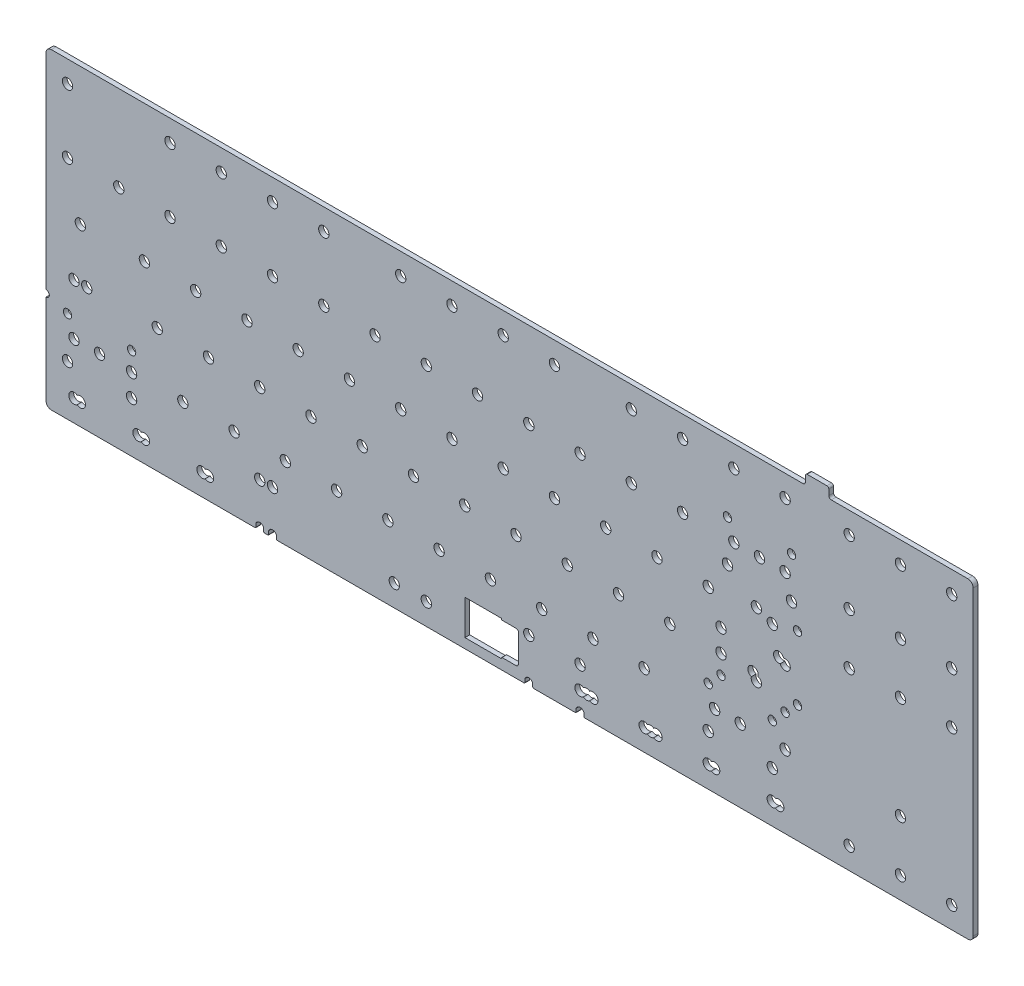
SolidWorks part; units mm, degrees
ref_plane "Front Plane" through (0, 0, 0) normal (0, 0, 1) x (1, 0, 0)
ref_plane "Top Plane" through (0, 0, 0) normal (0, 1, 0) x (1, 0, 0)
ref_plane "Right Plane" through (0, 0, 0) normal (1, 0, 0) x (0, 0, -1)
sketch "Model" plane through (0, 0, 0) normal (0, 0, 1) x (1, 0, 0)
  line L0 (147.7, -67.6) -> (161.2775, -67.6)
  line L1 (161.3, -67.8) -> (161.3, -67.9)
  line L2 (161.5, -68.1) -> (166.7, -68.1)
  line L3 (167.6, -69) -> (167.6, -79.2)
  line L4 (166.7, -80.1) -> (161.5, -80.1)
  line L5 (161.3, -80.3) -> (161.3, -80.4)
  line L6 (161.2775, -80.6) -> (147.7, -80.6)
  line L7 (147.7, -80.6) -> (147.7, -67.6)
  line L12 (273.3562, 31.8125) -> (-6, 31.8125)
  line L13 (-8, 29.8125) -> (-8, -46.4)
  line L14 (-7.998, -48.85) -> (-8, -48.85)
  line L15 (-8, -48.85) -> (-8, -82.2)
  line L16 (-6, -84.2) -> (69.7, -84.2)
  line L17 (70, -83.9) -> (70, -82.6265)
  line L18 (74.75, -82.6523) -> (74.75, -83.9)
  line L19 (74.45, -84.2) -> (73.2, -84.2)
  line L20 (72.9, -83.9) -> (72.9, -82.6795)
  line L21 (170, -82.6523) -> (170, -83.9)
  line L22 (169.7, -84.2) -> (77.95, -84.2)
  line L23 (77.65, -83.9) -> (77.65, -82.6523)
  line L24 (189.05, -82.6523) -> (189.05, -83.9)
  line L25 (188.75, -84.2) -> (173.2, -84.2)
  line L26 (172.9, -83.9) -> (172.9, -82.6523)
  line L27 (283.8562, 31.8125) -> (334.6125, 31.8125)
  line L28 (336.6125, 29.8125) -> (336.6125, -82.2)
  line L29 (334.6125, -84.2) -> (192.25, -84.2)
  line L30 (191.95, -83.9) -> (191.95, -82.6523)
  line L31 (282.9563, 32.7125) -> (282.9563, 34.85)
  line L32 (282.2563, 35.55) -> (274.9563, 35.55)
  line L33 (274.2563, 34.85) -> (274.2563, 32.7125)
  circle A0 centre (223.8375, -38.1) radius 1.925
  circle A1 centre (176.2125, -57.15) radius 1.925
  circle A2 centre (209.55, 0) radius 1.925
  circle A3 centre (195.2625, -57.15) radius 1.925
  circle A4 centre (214.3125, -57.15) radius 1.925
  circle A5 centre (190.5, 0) radius 1.925
  circle A6 centre (19.05, 0) radius 1.925
  circle A7 centre (38.1, 0) radius 1.925
  circle A8 centre (57.15, 0) radius 1.925
  circle A9 centre (76.2, 0) radius 1.925
  circle A10 centre (95.25, 0) radius 1.925
  circle A11 centre (114.3, 0) radius 1.925
  circle A12 centre (133.35, 0) radius 1.925
  circle A13 centre (152.4, 0) radius 1.925
  circle A14 centre (171.45, 0) radius 1.925
  circle A15 centre (204.7875, -38.1) radius 1.925
  circle A16 centre (228.6, 0) radius 1.925
  circle A17 centre (33.3375, -38.1) radius 1.925
  circle A18 centre (119.0625, -57.15) radius 1.925
  circle A19 centre (266.7, 0) radius 1.925
  circle A20 centre (80.9625, -57.15) radius 1.925
  circle A21 centre (2.3813, -38.1) radius 1.925
  circle A22 centre (7.1438, -38.1) radius 1.925
  circle A23 centre (71.4375, -38.1) radius 1.925
  circle A24 centre (290.5125, -19.05) radius 1.925
  circle A25 centre (309.5625, -76.2) radius 1.925
  circle A26 centre (66.675, -19.05) radius 1.925
  circle A27 centre (309.5625, -19.05) radius 1.925
  arc A28 (256.6362, -38.658) -> (254.1764, -39.9233) centre (254.7938, -38.1) ccw
  circle A29 centre (0, 23.8125) radius 1.925
  circle A30 centre (90.4875, -38.1) radius 1.925
  circle A31 centre (38.1, 23.8125) radius 1.925
  circle A32 centre (57.15, 23.8125) radius 1.925
  circle A33 centre (76.2, 23.8125) radius 1.925
  circle A34 centre (95.25, 23.8125) radius 1.925
  circle A35 centre (123.825, 23.8125) radius 1.925
  circle A36 centre (142.875, 23.8125) radius 1.925
  circle A37 centre (161.925, 23.8125) radius 1.925
  circle A38 centre (180.975, 23.8125) radius 1.925
  circle A39 centre (209.55, 23.8125) radius 1.925
  circle A40 centre (228.6, 23.8125) radius 1.925
  circle A41 centre (247.65, 23.8125) radius 1.925
  circle A42 centre (266.7, 23.8125) radius 1.925
  circle A43 centre (266.7, -57.15) radius 1.925
  circle A44 centre (109.5375, -38.1) radius 1.925
  circle A45 centre (128.5875, -38.1) radius 1.925
  circle A46 centre (309.5625, 0) radius 1.925
  circle A47 centre (161.925, -19.05) radius 1.925
  circle A48 centre (290.5125, 0) radius 1.925
  circle A49 centre (23.8125, -57.15) radius 1.925
  circle A50 centre (147.6375, -38.1) radius 1.925
  circle A51 centre (166.6875, -38.1) radius 1.925
  circle A52 centre (185.7375, -38.1) radius 1.925
  arc A53 (51.1969, -74.6874) -> (51.1969, -77.7126) centre (50.0063, -76.2) ccw
  arc A54 (51.1969, -77.7126) -> (51.1969, -74.6874) centre (52.3875, -76.2) ccw
  arc A55 (3.5719, -74.6874) -> (3.5719, -77.7126) centre (2.3813, -76.2) ccw
  arc A56 (3.5719, -77.7126) -> (3.5719, -74.6874) centre (4.7625, -76.2) ccw
  circle A57 centre (2.3813, -57.15) radius 1.925
  arc A58 (27.3844, -74.6874) -> (27.3844, -77.7126) centre (26.1938, -76.2) ccw
  arc A59 (27.3844, -77.7126) -> (27.3844, -74.6874) centre (28.575, -76.2) ccw
  circle A60 centre (290.5125, -76.2) radius 1.925
  circle A61 centre (157.1625, -57.15) radius 1.925
  arc A62 (239.3157, -74.6874) -> (239.3157, -77.7126) centre (238.125, -76.2) ccw
  arc A63 (239.3157, -77.7126) -> (239.3157, -74.6874) centre (240.5063, -76.2) ccw
  circle A64 centre (247.65, 0) radius 1.925
  circle A65 centre (121.4438, -76.2) radius 1.925
  circle A66 centre (240.5063, -57.15) radius 1.925
  circle A67 centre (242.8875, -38.1) radius 1.925
  arc A68 (266.1421, -27.9576) -> (264.8767, -30.4174) centre (264.3188, -28.575) ccw
  circle A69 centre (257.175, 0) radius 1.925
  circle A70 centre (11.9062, -57.15) radius 1.925
  circle A71 centre (138.1125, -57.15) radius 1.925
  circle A72 centre (180.975, -19.05) radius 1.925
  circle A73 centre (200.025, -19.05) radius 1.925
  circle A74 centre (328.6125, 23.8125) radius 1.925
  circle A75 centre (328.6125, -19.05) radius 1.925
  circle A76 centre (328.6125, 0) radius 1.925
  circle A77 centre (290.5125, 23.8125) radius 1.925
  circle A78 centre (28.575, -19.05) radius 1.925
  circle A79 centre (85.725, -19.05) radius 1.925
  arc A80 (191.6907, -74.6874) -> (191.6907, -77.7126) centre (190.5, -76.2) ccw
  arc A81 (191.6907, -77.7126) -> (194.0719, -77.7126) centre (192.8813, -76.2) ccw
  arc A82 (194.0719, -77.7126) -> (194.0719, -74.6874) centre (195.2625, -76.2) ccw
  arc A83 (263.1282, -74.6874) -> (263.1282, -77.7126) centre (261.9375, -76.2) ccw
  arc A84 (263.1282, -77.7126) -> (263.1282, -74.6874) centre (264.3188, -76.2) ccw
  circle A85 centre (250.0312, -57.15) radius 1.925
  arc A86 (215.5032, -74.6874) -> (215.5032, -77.7126) centre (214.3125, -76.2) ccw
  arc A87 (215.5032, -77.7126) -> (217.8844, -77.7126) centre (216.6938, -76.2) ccw
  arc A88 (217.8844, -77.7126) -> (217.8844, -74.6874) centre (219.075, -76.2) ccw
  circle A89 centre (328.6125, -76.2) radius 1.925
  circle A90 centre (52.3875, -38.1) radius 1.925
  circle A91 centre (309.5625, 23.8125) radius 1.925
  circle A92 centre (133.35, -76.2) radius 1.925
  circle A93 centre (76.2, -67.9) radius 1.925
  circle A94 centre (190.5, -67.9) radius 1.925
  arc A95 (77.65, -82.6523) -> (74.75, -82.6523) centre (76.2, -83.2) ccw
  arc A96 (191.95, -82.6523) -> (189.05, -82.6523) centre (190.5, -83.2) ccw
  circle A97 centre (71.44, -67.9) radius 1.925
  circle A98 centre (171.45, -67.9) radius 1.925
  arc A99 (72.9, -82.6795) -> (70, -82.6265) centre (71.44, -83.2) ccw
  arc A100 (172.9, -82.6523) -> (170, -82.6523) centre (171.45, -83.2) ccw
  circle A101 centre (0, -50.15) radius 1.55
  circle A102 centre (23.8125, -50.15) radius 1.55
  circle A103 centre (23.8125, -65.45) radius 1.925
  circle A104 centre (0, -65.45) radius 1.925
  circle A105 centre (245.2688, 7) radius 1.55
  circle A106 centre (269.0813, 7) radius 1.55
  circle A107 centre (269.0813, -8.3) radius 1.925
  circle A108 centre (245.2688, -8.3) radius 1.925
  circle A109 centre (266.7, -45.1) radius 1.55
  circle A110 centre (242.8875, -45.1) radius 1.55
  circle A111 centre (242.8875, -29.8) radius 1.925
  arc A112 (264.8767, -30.4174) -> (266.1421, -27.9576) centre (266.7, -29.8) ccw
  circle A113 centre (238.125, -50.15) radius 1.55
  circle A114 centre (261.9375, -50.15) radius 1.55
  circle A115 centre (261.9375, -65.45) radius 1.925
  circle A116 centre (238.125, -65.45) radius 1.925
  circle A117 centre (271.3188, -16.6687) radius 1.55
  circle A118 centre (271.3188, -40.4813) radius 1.55
  arc A119 (254.1764, -39.9233) -> (256.6362, -38.658) centre (256.0188, -40.4813) ccw
  circle A120 centre (256.0188, -16.6687) radius 1.925
  circle A121 centre (104.775, -19.05) radius 1.925
  circle A122 centre (4.7625, -19.05) radius 1.925
  circle A123 centre (142.875, -19.05) radius 1.925
  circle A124 centre (309.5625, -57.15) radius 1.925
  circle A125 centre (100.0125, -57.15) radius 1.925
  circle A126 centre (47.625, -19.05) radius 1.925
  circle A127 centre (61.9125, -57.15) radius 1.925
  circle A128 centre (123.825, -19.05) radius 1.925
  circle A129 centre (42.8625, -57.15) radius 1.925
  circle A130 centre (219.075, -19.05) radius 1.925
  circle A131 centre (261.9375, -19.05) radius 1.925
  circle A132 centre (238.125, -19.05) radius 1.925
  circle A133 centre (0, 0) radius 1.925
  arc A134 (161.3, -67.8) -> (161.2775, -67.6) centre (160.4, -67.8) ccw
  arc A135 (161.3, -67.9) -> (161.5, -68.1) centre (161.5, -67.9) ccw
  arc A136 (167.6, -69) -> (166.7, -68.1) centre (166.7, -69) ccw
  arc A137 (166.7, -80.1) -> (167.6, -79.2) centre (166.7, -79.2) ccw
  arc A138 (161.5, -80.1) -> (161.3, -80.3) centre (161.5, -80.3) ccw
  arc A139 (161.2775, -80.6) -> (161.3, -80.4) centre (160.4, -80.4) ccw
  arc A140 (194.0719, -74.6874) -> (191.6907, -74.6874) centre (192.8813, -76.2) ccw
  arc A141 (217.8844, -74.6874) -> (215.5032, -74.6874) centre (216.6938, -76.2) ccw
  arc A144 (273.3562, 31.8125) -> (274.2563, 32.7125) centre (273.3563, 32.7125) ccw
  arc A145 (-6, 31.8125) -> (-8, 29.8125) centre (-6, 29.8125) ccw
  arc A146 (-6.774, -47.626) -> (-8, -46.4) centre (-8, -47.626) ccw
  arc A147 (-7.998, -48.85) -> (-6.774, -47.626) centre (-7.998, -47.626) ccw
  arc A148 (-8, -82.2) -> (-6, -84.2) centre (-6, -82.2) ccw
  arc A149 (69.7, -84.2) -> (70, -83.9) centre (69.7, -83.9) ccw
  arc A150 (74.45, -84.2) -> (74.75, -83.9) centre (74.45, -83.9) ccw
  arc A151 (72.9, -83.9) -> (73.2, -84.2) centre (73.2, -83.9) ccw
  arc A152 (169.7, -84.2) -> (170, -83.9) centre (169.7, -83.9) ccw
  arc A153 (77.65, -83.9) -> (77.95, -84.2) centre (77.95, -83.9) ccw
  arc A154 (188.75, -84.2) -> (189.05, -83.9) centre (188.75, -83.9) ccw
  arc A155 (172.9, -83.9) -> (173.2, -84.2) centre (173.2, -83.9) ccw
  arc A156 (282.9563, 32.7125) -> (283.8562, 31.8125) centre (283.8563, 32.7125) ccw
  arc A157 (336.6125, 29.8125) -> (334.6125, 31.8125) centre (334.6125, 29.8125) ccw
  arc A158 (334.6125, -84.2) -> (336.6125, -82.2) centre (334.6125, -82.2) ccw
  arc A159 (191.95, -83.9) -> (192.25, -84.2) centre (192.25, -83.9) ccw
  arc A160 (282.9563, 34.85) -> (282.2563, 35.55) centre (282.2563, 34.85) ccw
  arc A161 (274.9563, 35.55) -> (274.2563, 34.85) centre (274.9563, 34.85) ccw
extrude "Boss-Extrude1" add sketch "Model" along normal blind 1.778
sketch "Sketch3" plane through (0, 0, 1.778) normal (0, 0, 1) x (1, 0, 0)
  point P0 (0, 23.8125)
  point P1 (38.1, 23.8125)
  point P3 (57.15, 23.8125)
  point P5 (76.2, 23.8125)
  point P7 (95.25, 23.8125)
  point P8 (123.825, 23.8125)
  point P9 (142.875, 23.8125)
  point P10 (161.925, 23.8125)
  point P11 (180.975, 23.8125)
  point P12 (209.55, 23.8125)
  point P13 (228.6, 23.8125)
  point P14 (247.65, 23.8125)
  point P15 (266.7, 23.8125)
  point P16 (290.5125, 23.8125)
  point P17 (309.5625, 23.8125)
  point P18 (328.6125, 23.8125)
  point P19 (290.5125, 0)
  point P20 (309.5625, 0)
  point P21 (328.6125, 0)
  point P22 (328.6125, -19.05)
  point P23 (309.5625, -19.05)
  point P24 (290.5125, -19.05)
  point P25 (309.5625, -57.15)
  point P26 (290.5125, -76.2)
  point P27 (309.5625, -76.2)
  point P28 (328.6125, -76.2)
  point P29 (264.3188, -76.2)
  point P30 (240.5063, -76.2)
  point P31 (219.075, -76.2)
  point P32 (195.2625, -76.2)
  point P33 (250.0312, -57.15)
  point P34 (214.3125, -57.15)
  point P35 (195.2625, -57.15)
  point P36 (176.2125, -57.15)
  point P37 (157.1625, -57.15)
  point P38 (138.1125, -57.15)
  point P39 (119.0625, -57.15)
  point P40 (100.0125, -57.15)
  point P41 (80.9625, -57.15)
  point P42 (133.35, -76.2)
  point P43 (61.9125, -57.15)
  point P44 (42.8625, -57.15)
  point P45 (11.9062, -57.15)
  point P46 (4.7625, -76.2)
  point P47 (28.575, -76.2)
  point P48 (52.3875, -76.2)
  point P49 (7.1438, -38.1)
  point P50 (4.7625, -19.05)
  point P51 (0, 0)
  point P52 (19.05, 0)
  point P53 (38.1, 0)
  point P54 (57.15, 0)
  point P55 (76.2, 0)
  point P56 (95.25, 0)
  point P57 (114.3, 0)
  point P58 (133.35, 0)
  point P59 (152.4, 0)
  point P60 (171.45, 0)
  point P61 (190.5, 0)
  point P62 (209.55, 0)
  point P63 (228.6, 0)
  point P64 (219.075, -19.05)
  point P65 (200.025, -19.05)
  point P66 (180.975, -19.05)
  point P67 (161.925, -19.05)
  point P68 (142.875, -19.05)
  point P69 (123.825, -19.05)
  point P70 (104.775, -19.05)
  point P71 (85.725, -19.05)
  point P72 (66.675, -19.05)
  point P73 (47.625, -19.05)
  point P74 (28.575, -19.05)
  point P75 (33.3375, -38.1)
  point P76 (52.3875, -38.1)
  point P77 (71.4375, -38.1)
  point P78 (90.4875, -38.1)
  point P79 (109.5375, -38.1)
  point P80 (128.5875, -38.1)
  point P81 (147.6375, -38.1)
  point P82 (166.6875, -38.1)
  point P83 (185.7375, -38.1)
  point P84 (204.7875, -38.1)
  point P85 (223.8375, -38.1)
